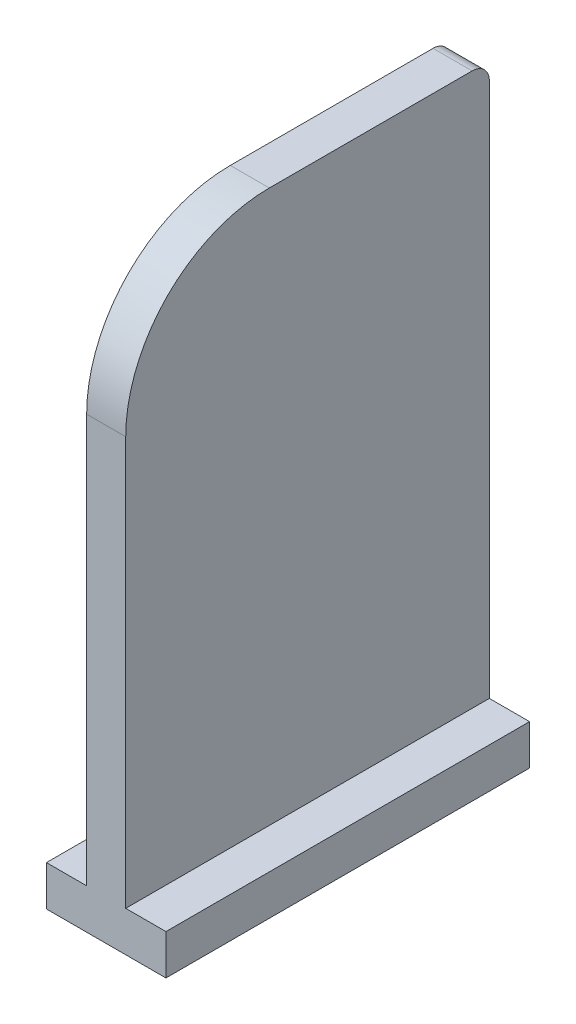
SolidWorks part; units mm, degrees
ref_plane "Front Plane" through (0, 0, 0) normal (0, 0, 1) x (1, 0, 0)
ref_plane "Top Plane" through (0, 0, 0) normal (0, 1, 0) x (1, 0, 0)
ref_plane "Right Plane" through (0, 0, 0) normal (1, 0, 0) x (0, 0, -1)
sketch "Sketch1" plane through (0, 0, 0) normal (0, 0, 1) x (1, 0, 0)
  line L0 (0, 7) -> (7, 7)
  line L1 (0, 0) -> (20.8, 0)
  line L2 (0, 0) -> (0, 7)
  line L4 (20.8, 0) -> (20.8, 7)
  line L6 (7, 7) -> (7, 18.1071)
  line L8 (13.8, 7) -> (13.8, 18.1071)
  line L10 (7, 18.1071) -> (7, 103.1)
  line L11 (7, 103.1) -> (13.8, 103.1)
  line L12 (13.8, 18.1071) -> (13.8, 103.1)
  line L13 (13.8, 7) -> (20.8, 7)
  dimension "D1" = 7
  dimension "D2" = 7
  dimension "D3" = 6.8
  dimension "D4" = 7
  dimension "D5" = 7
  dimension "D6" = 103.1
extrude "Boss-Extrude1" add sketch "Sketch1" along normal blind 63.3
sketch "Sketch2" plane through (0, 0, 0) normal (0, 0, 1) x (1, 0, 0)
  line L0 (7, 18.78) -> (13.8, 18.78)
  line L1 (7, 103.1) -> (7, 7) construction
  line L2 (13.8, 7) -> (13.8, 103.1) construction
  line L3 (20.8, 7) -> (13.8, 7) construction
  line L5 (7, 18.78) -> (13.8, 18.78)
  line L6 (7, 18.78) -> (7, 103.1)
  line L7 (7, 103.1) -> (13.8, 103.1)
  line L8 (13.8, 18.78) -> (13.8, 103.1)
  dimension "D1" = 11.78
fillet "Fillet4" radius 3 1 edges at (10.4, 103.1, 0)
fillet "Fillet5" radius 25 1 edges at (10.4, 103.1, 63.3)
